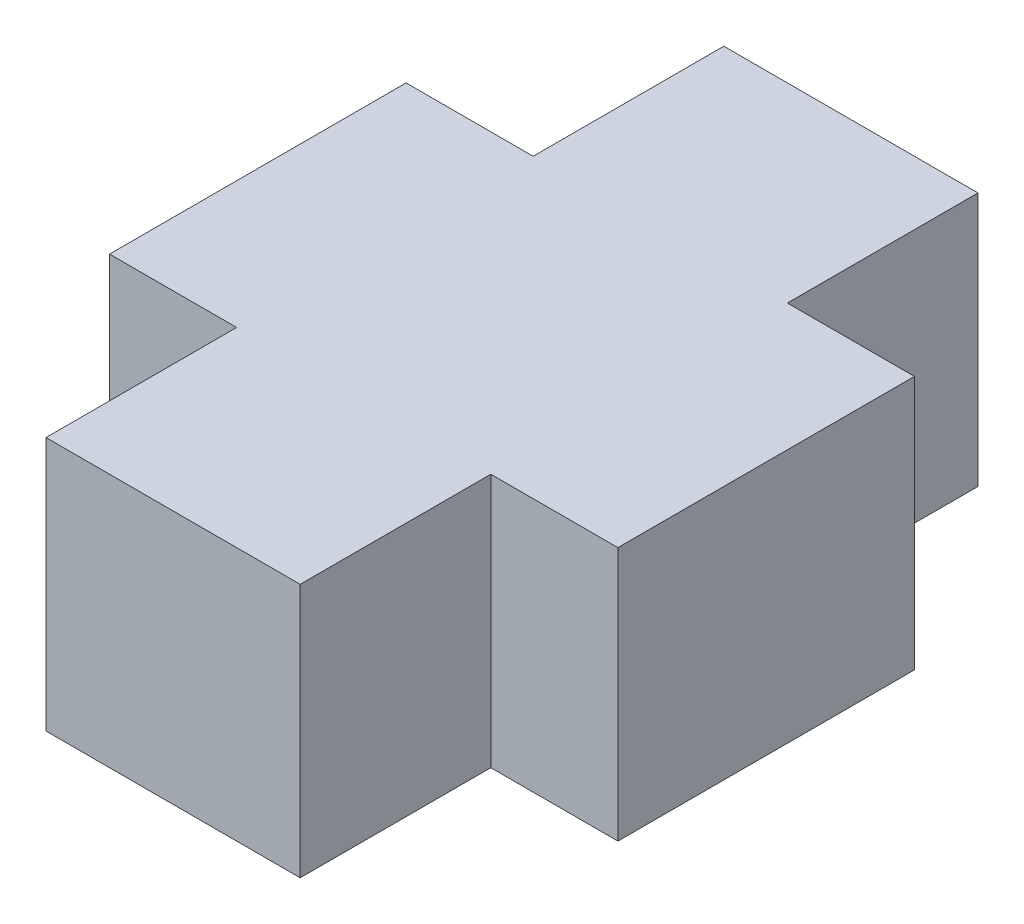
SolidWorks part; units mm, degrees
ref_plane "Front Plane" through (0, 0, 0) normal (0, 0, 1) x (1, 0, 0)
ref_plane "Top Plane" through (0, 0, 0) normal (0, 1, 0) x (1, 0, 0)
ref_plane "Right Plane" through (0, 0, 0) normal (1, 0, 0) x (0, 0, -1)
sketch "Sketch1" plane through (0, 0, 0) normal (0, 1, 0) x (1, 0, 0)
  line L1 (-38.1, -101.6) -> (38.1, -101.6)
  line L2 (-38.1, -101.6) -> (-38.1, 101.6)
  line L3 (-38.1, 101.6) -> (38.1, 101.6)
  line L4 (38.1, -101.6) -> (38.1, 101.6)
  line L5 (-38.1, -101.6) -> (38.1, 101.6) construction
  line L6 (-38.1, 101.6) -> (38.1, -101.6) construction
  line L7 (76.2, -44.45) -> (-76.2, -44.45)
  line L8 (76.2, -44.45) -> (76.2, 44.45)
  line L9 (76.2, 44.45) -> (-76.2, 44.45)
  line L10 (-76.2, -44.45) -> (-76.2, 44.45)
  line L11 (76.2, -44.45) -> (-76.2, 44.45) construction
  line L12 (76.2, 44.45) -> (-76.2, -44.45) construction
  point P0 (0, 0)
  point P6 (0, 0)
  dimension "D1" = 203.2
  dimension "D2" = 76.2
  dimension "D3" = 88.9
  dimension "D4" = 152.4
extrude "Boss-Extrude1" add sketch "Sketch1" along normal blind 76.2 contours L4 L9 L2 L7 | L9 L4 L3 L2 | L8 L9 L4 L7 | L4 L7 L2 L1 | L10 L7 L2 L9
